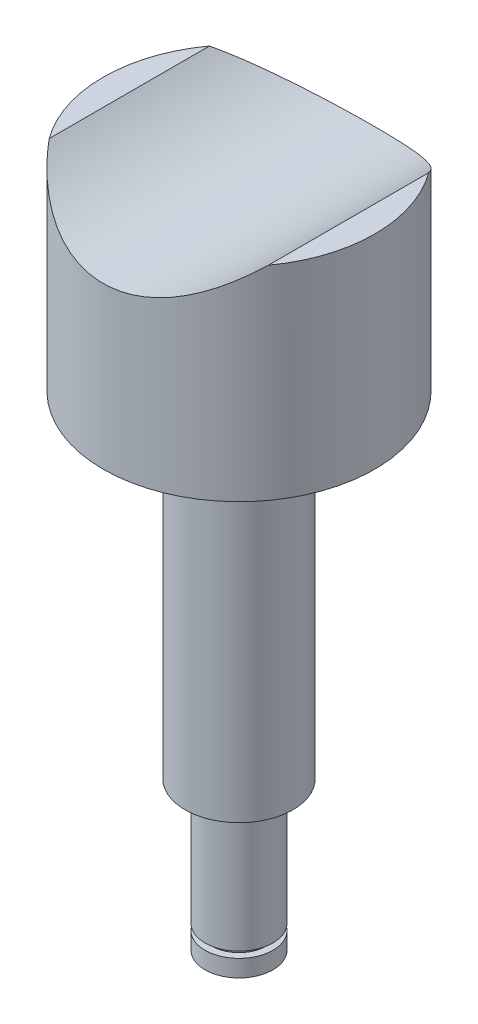
SolidWorks part; units mm, degrees
ref_plane "Front" through (0, 0, 0) normal (0, 0, 1) x (1, 0, 0)
ref_plane "Top" through (0, 0, 0) normal (0, 1, 0) x (1, 0, 0)
ref_plane "Right" through (0, 0, 0) normal (1, 0, 0) x (0, 0, -1)
sketch "Sketch1" plane through (0, 0, 0) normal (0, 1, 0) x (1, 0, 0)
  circle A0 centre (0, 0) radius 16
extrude "Boss-Extrude1" add sketch "Sketch1" along normal blind 24
sketch "Sketch2" plane through (0, 0, 0) normal (0, -1, 0) x (1, 0, 0)
  circle A0 centre (0, 0) radius 6.35
extrude "Boss-Extrude2" add sketch "Sketch2" along normal blind 39.57
sketch "Sketch3" plane through (0, -39.57, 0) normal (0, -1, 0) x (1, 0, 0)
  circle A0 centre (0, 0) radius 4
extrude "Boss-Extrude3" add sketch "Sketch3" along normal blind 17.5
sketch "Sketch4" plane through (0, 0, 0) normal (0, 0, 1) x (1, 0, 0)
  circle A0 centre (0, 38) radius 19.05
  dimension "D1" = 38
extrude "Cut-Extrude1" cut sketch "Sketch4" against normal through all both and the other way through all
sketch "Sketch5" plane through (0, -57.07, 0) normal (0, -1, 0) x (1, 0, 0)
  circle A0 centre (0, 0) radius 3.175
  circle A1 centre (0, 0) radius 4.571
extrude "Cut-Extrude2" cut sketch "Sketch5" against normal blind 0.74 from offset 2
